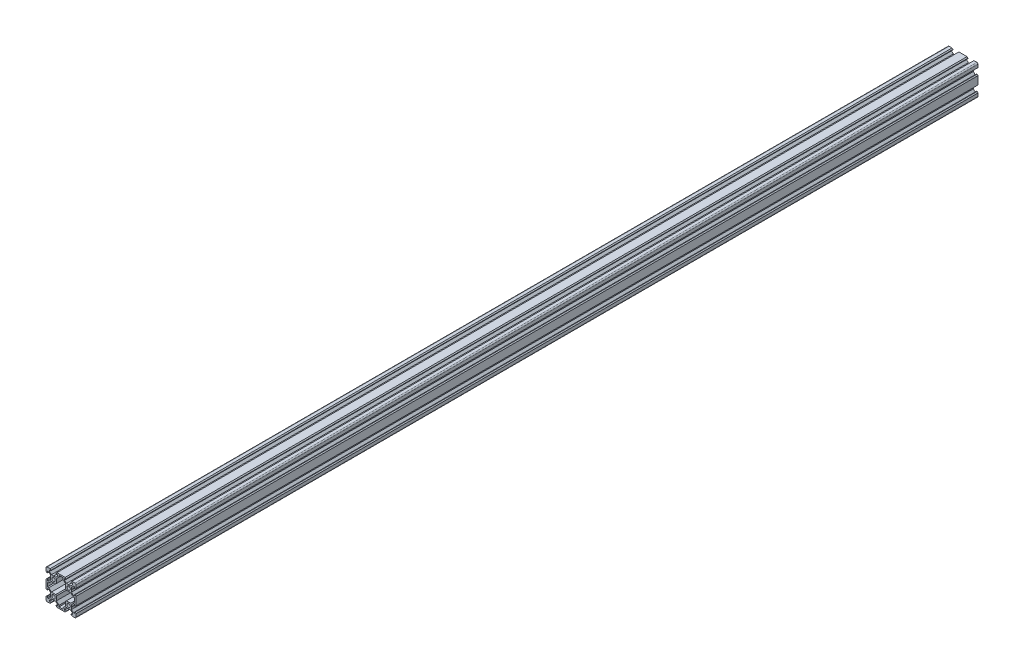
SolidWorks part; units mm, degrees
material "6061-T6 (SS)"
ref_plane "Front Plane" through (0, 0, 0) normal (0, 0, 1) x (1, 0, 0)
ref_plane "Top Plane" through (0, 0, 0) normal (0, 1, 0) x (1, 0, 0)
ref_plane "Right Plane" through (0, 0, 0) normal (1, 0, 0) x (0, 0, -1)
sketch "Sketch1" plane through (0, 0, 0) normal (0, 0, 1) x (1, 0, 0)
  line L1 (18.5, -20) -> (-18.5, -20)
  line L2 (20, -18.5) -> (20, 18.5)
  line L3 (18.5, 20) -> (-18.5, 20)
  line L4 (-20, -18.5) -> (-20, 18.5)
  line L5 (20, -20) -> (-20, 20) construction
  line L6 (20, 20) -> (-20, -20) construction
  circle A0 centre (-10, 10) radius 2.3
  circle A1 centre (10, -10) radius 2.3
  circle A2 centre (10, 10) radius 2.3
  circle A3 centre (-10, -10) radius 2.3
  arc A4 (-18.5, -20) -> (-20, -18.5) centre (-18.5, -18.5) cw
  arc A5 (18.5, -20) -> (20, -18.5) centre (18.5, -18.5) ccw
  arc A6 (20, 18.5) -> (18.5, 20) centre (18.5, 18.5) ccw
  arc A7 (-18.5, 20) -> (-20, 18.5) centre (-18.5, 18.5) ccw
  point P0 (0, 0)
  line B0 (-10, 10) -> (-10, 20) construction
  line B1 (-10, 13.69) -> (-10.21, 13.9)
  line B2 (-10.21, 13.9) -> (-12.8393, 13.9)
  line B3 (-12.8393, 13.9) -> (-15.5, 16.5607)
  line B4 (-15.5, 16.5607) -> (-15.5, 18.2)
  line B5 (-15.5, 18.2) -> (-13.395, 18.2)
  line B6 (-13.395, 18.2) -> (-13.395, 18.815)
  line B7 (-13.395, 18.815) -> (-14.58, 20)
  line B8 (-14.58, 20) -> (-5.42, 20)
  line B9 (-10, 10) -> (-15.9132, 15.9132) construction
  line B10 (-6.605, 18.815) -> (-5.42, 20)
  line B11 (-6.605, 18.2) -> (-6.605, 18.815)
  line B12 (-4.5, 18.2) -> (-6.605, 18.2)
  line B13 (-4.5, 16.5607) -> (-4.5, 18.2)
  line B14 (-7.1607, 13.9) -> (-4.5, 16.5607)
  line B15 (-9.79, 13.9) -> (-7.1607, 13.9)
  line B16 (-10, 13.69) -> (-9.79, 13.9)
  line B17 (10, 10) -> (10, 20) construction
  line B18 (10, 13.69) -> (9.79, 13.9)
  line B19 (9.79, 13.9) -> (7.1607, 13.9)
  line B20 (7.1607, 13.9) -> (4.5, 16.5607)
  line B21 (4.5, 16.5607) -> (4.5, 18.2)
  line B22 (4.5, 18.2) -> (6.605, 18.2)
  line B23 (6.605, 18.2) -> (6.605, 18.815)
  line B24 (6.605, 18.815) -> (5.42, 20)
  line B25 (5.42, 20) -> (14.58, 20)
  line B26 (10, 10) -> (4.0868, 15.9132) construction
  line B27 (13.395, 18.815) -> (14.58, 20)
  line B28 (13.395, 18.2) -> (13.395, 18.815)
  line B29 (15.5, 18.2) -> (13.395, 18.2)
  line B30 (15.5, 16.5607) -> (15.5, 18.2)
  line B31 (12.8393, 13.9) -> (15.5, 16.5607)
  line B32 (10.21, 13.9) -> (12.8393, 13.9)
  line B33 (10, 13.69) -> (10.21, 13.9)
  line B34 (-10, 10) -> (-20, 10) construction
  line B35 (-13.69, 10) -> (-13.9, 9.79)
  line B36 (-13.9, 9.79) -> (-13.9, 7.1607)
  line B37 (-13.9, 7.1607) -> (-16.5607, 4.5)
  line B38 (-16.5607, 4.5) -> (-18.2, 4.5)
  line B39 (-18.2, 4.5) -> (-18.2, 6.605)
  line B40 (-18.2, 6.605) -> (-18.815, 6.605)
  line B41 (-18.815, 6.605) -> (-20, 5.42)
  line B42 (-20, 5.42) -> (-20, 14.58)
  line B43 (-10, 10) -> (-15.9132, 4.0868) construction
  line B44 (-18.815, 13.395) -> (-20, 14.58)
  line B45 (-18.2, 13.395) -> (-18.815, 13.395)
  line B46 (-18.2, 15.5) -> (-18.2, 13.395)
  line B47 (-16.5607, 15.5) -> (-18.2, 15.5)
  line B48 (-13.9, 12.8393) -> (-16.5607, 15.5)
  line B49 (-13.9, 10.21) -> (-13.9, 12.8393)
  line B50 (-13.69, 10) -> (-13.9, 10.21)
  line B51 (-10, -10) -> (-20, -10) construction
  line B52 (-13.69, -10) -> (-13.9, -10.21)
  line B53 (-13.9, -10.21) -> (-13.9, -12.8393)
  line B54 (-13.9, -12.8393) -> (-16.5607, -15.5)
  line B55 (-16.5607, -15.5) -> (-18.2, -15.5)
  line B56 (-18.2, -15.5) -> (-18.2, -13.395)
  line B57 (-18.2, -13.395) -> (-18.815, -13.395)
  line B58 (-18.815, -13.395) -> (-20, -14.58)
  line B59 (-20, -14.58) -> (-20, -5.42)
  line B60 (-10, -10) -> (-15.9132, -15.9132) construction
  line B61 (-18.815, -6.605) -> (-20, -5.42)
  line B62 (-18.2, -6.605) -> (-18.815, -6.605)
  line B63 (-18.2, -4.5) -> (-18.2, -6.605)
  line B64 (-16.5607, -4.5) -> (-18.2, -4.5)
  line B65 (-13.9, -7.1607) -> (-16.5607, -4.5)
  line B66 (-13.9, -9.79) -> (-13.9, -7.1607)
  line B67 (-13.69, -10) -> (-13.9, -9.79)
  line B68 (-10, -10) -> (-10, -20) construction
  line B69 (-10, -13.69) -> (-9.79, -13.9)
  line B70 (-9.79, -13.9) -> (-7.1607, -13.9)
  line B71 (-7.1607, -13.9) -> (-4.5, -16.5607)
  line B72 (-4.5, -16.5607) -> (-4.5, -18.2)
  line B73 (-4.5, -18.2) -> (-6.605, -18.2)
  line B74 (-6.605, -18.2) -> (-6.605, -18.815)
  line B75 (-6.605, -18.815) -> (-5.42, -20)
  line B76 (-5.42, -20) -> (-14.58, -20)
  line B77 (-10, -10) -> (-4.0868, -15.9132) construction
  line B78 (-13.395, -18.815) -> (-14.58, -20)
  line B79 (-13.395, -18.2) -> (-13.395, -18.815)
  line B80 (-15.5, -18.2) -> (-13.395, -18.2)
  line B81 (-15.5, -16.5607) -> (-15.5, -18.2)
  line B82 (-12.8393, -13.9) -> (-15.5, -16.5607)
  line B83 (-10.21, -13.9) -> (-12.8393, -13.9)
  line B84 (-10, -13.69) -> (-10.21, -13.9)
  line B85 (10, -10) -> (10, -20) construction
  line B86 (10, -13.69) -> (10.21, -13.9)
  line B87 (10.21, -13.9) -> (12.8393, -13.9)
  line B88 (12.8393, -13.9) -> (15.5, -16.5607)
  line B89 (15.5, -16.5607) -> (15.5, -18.2)
  line B90 (15.5, -18.2) -> (13.395, -18.2)
  line B91 (13.395, -18.2) -> (13.395, -18.815)
  line B92 (13.395, -18.815) -> (14.58, -20)
  line B93 (14.58, -20) -> (5.42, -20)
  line B94 (10, -10) -> (15.9132, -15.9132) construction
  line B95 (6.605, -18.815) -> (5.42, -20)
  line B96 (6.605, -18.2) -> (6.605, -18.815)
  line B97 (4.5, -18.2) -> (6.605, -18.2)
  line B98 (4.5, -16.5607) -> (4.5, -18.2)
  line B99 (7.1607, -13.9) -> (4.5, -16.5607)
  line B100 (9.79, -13.9) -> (7.1607, -13.9)
  line B101 (10, -13.69) -> (9.79, -13.9)
  line B102 (10, 10) -> (20, 10) construction
  line B103 (13.69, 10) -> (13.9, 10.21)
  line B104 (13.9, 10.21) -> (13.9, 12.8393)
  line B105 (13.9, 12.8393) -> (16.5607, 15.5)
  line B106 (16.5607, 15.5) -> (18.2, 15.5)
  line B107 (18.2, 15.5) -> (18.2, 13.395)
  line B108 (18.2, 13.395) -> (18.815, 13.395)
  line B109 (18.815, 13.395) -> (20, 14.58)
  line B110 (20, 14.58) -> (20, 5.42)
  line B111 (10, 10) -> (15.9132, 15.9132) construction
  line B112 (18.815, 6.605) -> (20, 5.42)
  line B113 (18.2, 6.605) -> (18.815, 6.605)
  line B114 (18.2, 4.5) -> (18.2, 6.605)
  line B115 (16.5607, 4.5) -> (18.2, 4.5)
  line B116 (13.9, 7.1607) -> (16.5607, 4.5)
  line B117 (13.9, 9.79) -> (13.9, 7.1607)
  line B118 (13.69, 10) -> (13.9, 9.79)
  line B119 (10, -10) -> (20, -10) construction
  line B120 (13.69, -10) -> (13.9, -9.79)
  line B121 (13.9, -9.79) -> (13.9, -7.1607)
  line B122 (13.9, -7.1607) -> (16.5607, -4.5)
  line B123 (16.5607, -4.5) -> (18.2, -4.5)
  line B124 (18.2, -4.5) -> (18.2, -6.605)
  line B125 (18.2, -6.605) -> (18.815, -6.605)
  line B126 (18.815, -6.605) -> (20, -5.42)
  line B127 (20, -5.42) -> (20, -14.58)
  line B128 (10, -10) -> (15.9132, -4.0868) construction
  line B129 (18.815, -13.395) -> (20, -14.58)
  line B130 (18.2, -13.395) -> (18.815, -13.395)
  line B131 (18.2, -15.5) -> (18.2, -13.395)
  line B132 (16.5607, -15.5) -> (18.2, -15.5)
  line B133 (13.9, -12.8393) -> (16.5607, -15.5)
  line B134 (13.9, -10.21) -> (13.9, -12.8393)
  line B135 (13.69, -10) -> (13.9, -10.21)
  line B136 (-18.2, -2.7) -> (-18.2, 2.7)
  line B137 (-18.2, 2.7) -> (-16.2393, 2.7)
  line B138 (-16.2393, 2.7) -> (-12.8393, 6.1)
  line B139 (-12.8393, 6.1) -> (-7.1607, 6.1)
  line B140 (-10, 6.1) -> (-10, 0) construction
  line B141 (-10, 0) -> (-18.2, 0) construction
  line B142 (-12.8393, -6.1) -> (-7.1607, -6.1)
  line B143 (-16.2393, -2.7) -> (-12.8393, -6.1)
  line B144 (-18.2, -2.7) -> (-16.2393, -2.7)
  line B145 (-10, 6.1) -> (-10, 10) construction
  line B146 (-10, 10) -> (-15.0927, 4.9073) construction
  line B147 (-10, 10) -> (-6.3747, 6.3747) construction
  line B148 (2.7, 18.2) -> (2.7, 16.2393)
  line B149 (2.7, 16.2393) -> (6.1, 12.8393)
  line B150 (6.1, 12.8393) -> (6.1, 7.1607)
  line B151 (-6.1, 12.8393) -> (-6.1, 7.1607)
  line B152 (-2.7, 16.2393) -> (-6.1, 12.8393)
  line B153 (-2.7, 18.2) -> (-2.7, 16.2393)
  line B154 (2.7, 18.2) -> (-2.7, 18.2)
  line B155 (2.7, -18.2) -> (-2.7, -18.2)
  line B156 (-2.7, -18.2) -> (-2.7, -16.2393)
  line B157 (-2.7, -16.2393) -> (-6.1, -12.8393)
  line B158 (-6.1, -12.8393) -> (-6.1, -7.1607)
  line B159 (6.1, -12.8393) -> (6.1, -7.1607)
  line B160 (2.7, -16.2393) -> (6.1, -12.8393)
  line B161 (2.7, -18.2) -> (2.7, -16.2393)
  line B162 (0, 18.2) -> (0, -18.2) construction
  line B163 (12.8393, -6.1) -> (7.1607, -6.1)
  line B164 (16.2393, -2.7) -> (12.8393, -6.1)
  line B165 (18.2, -2.7) -> (16.2393, -2.7)
  line B166 (18.2, -2.7) -> (18.2, 2.7)
  line B167 (18.2, 2.7) -> (16.2393, 2.7)
  line B168 (16.2393, 2.7) -> (12.8393, 6.1)
  line B169 (12.8393, 6.1) -> (7.1607, 6.1)
  line B170 (-7.1607, 6.1) -> (-6.1, 7.1607)
  line B171 (6.1, 7.1607) -> (7.1607, 6.1)
  line B172 (7.1607, -6.1) -> (6.1, -7.1607)
  line B173 (-6.1, -7.1607) -> (-7.1607, -6.1)
  dimension "D4" = 4.6
  dimension "D5" = 1.5
  dimension "D1" = 40
  dimension "D2" = 10
  dimension "D3" = 10
sketch_block_instance "V Slot 2-1"
sketch_block "V Slot 2" parameters "D1"=10, "D2"=11, "D3"=4.3, "D4"=1.8, "D5"=0.21, "D6"=45, "D7"=9.16, "D8"=1.5, "D9"=6.79
sketch_block_instance "V Slot 2-2"
sketch_block_instance "V Slot 2-3"
sketch_block_instance "V Slot 2-4"
sketch_block_instance "V Slot 2-5"
sketch_block_instance "V Slot 2-6"
sketch_block_instance "V Slot 2-7"
sketch_block_instance "V Slot 2-8"
sketch_block_instance "Center Cutout 2-1"
sketch_block "Center Cutout 2" parameters "D1"=5.4, "D2"=12.2, "D3"=8.2, "D4"=45, "D5"=10, "D6"=1.5
extrude "Boss-Extrude1" add sketch "Sketch1" along normal blind 1200 contours B135 B120 B121 B122 B123 B124 B125 B126 L2 B112 B113 B114 B115 B116 B117 B118 B103 B104 B105 B106 B107 B108 B109 A6 L3 B27 B28 B29 B30 B31 B32 B33 B18 B19 B20 B21 B22 B23 B24 B10 B11 B12 B13 B14 B15 B16 B1 B2 B3
